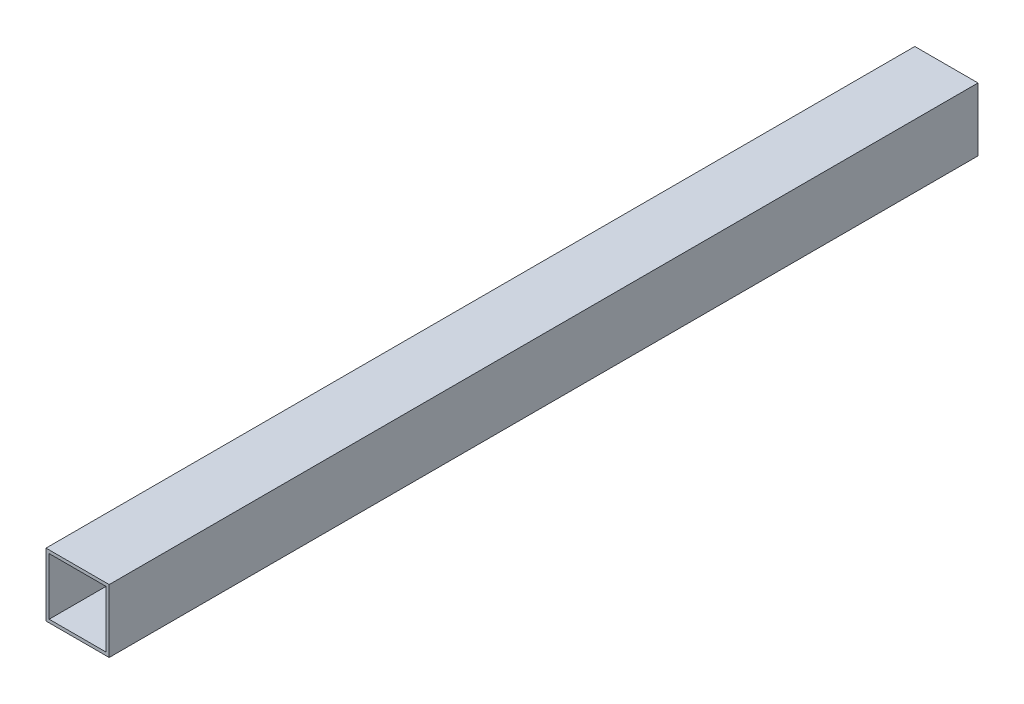
SolidWorks part; units mm, degrees
ref_plane "Front Plane" through (0, 0, 0) normal (0, 0, 1) x (1, 0, 0)
ref_plane "Top Plane" through (0, 0, 0) normal (0, 1, 0) x (1, 0, 0)
ref_plane "Right Plane" through (0, 0, 0) normal (1, 0, 0) x (0, 0, -1)
sketch "Sketch1" plane through (0, 0, 0) normal (0, 0, 1) x (1, 0, 0)
  line L0 (-927, 1629.5) -> (-963, 1629.5)
  line L1 (-925, 1631.5) -> (-965, 1631.5)
  line L2 (-925, 1631.5) -> (-925, 1591.5)
  line L3 (-925, 1591.5) -> (-965, 1591.5)
  line L4 (-965, 1631.5) -> (-965, 1591.5)
  line L5 (-963, 1629.5) -> (-963, 1593.5)
  line L6 (-927, 1593.5) -> (-963, 1593.5)
  line L7 (-927, 1629.5) -> (-927, 1593.5)
  dimension "D1" = 2
extrude "Boss-Extrude1" add sketch "Sketch1" along normal up to surface (550 mm away)
